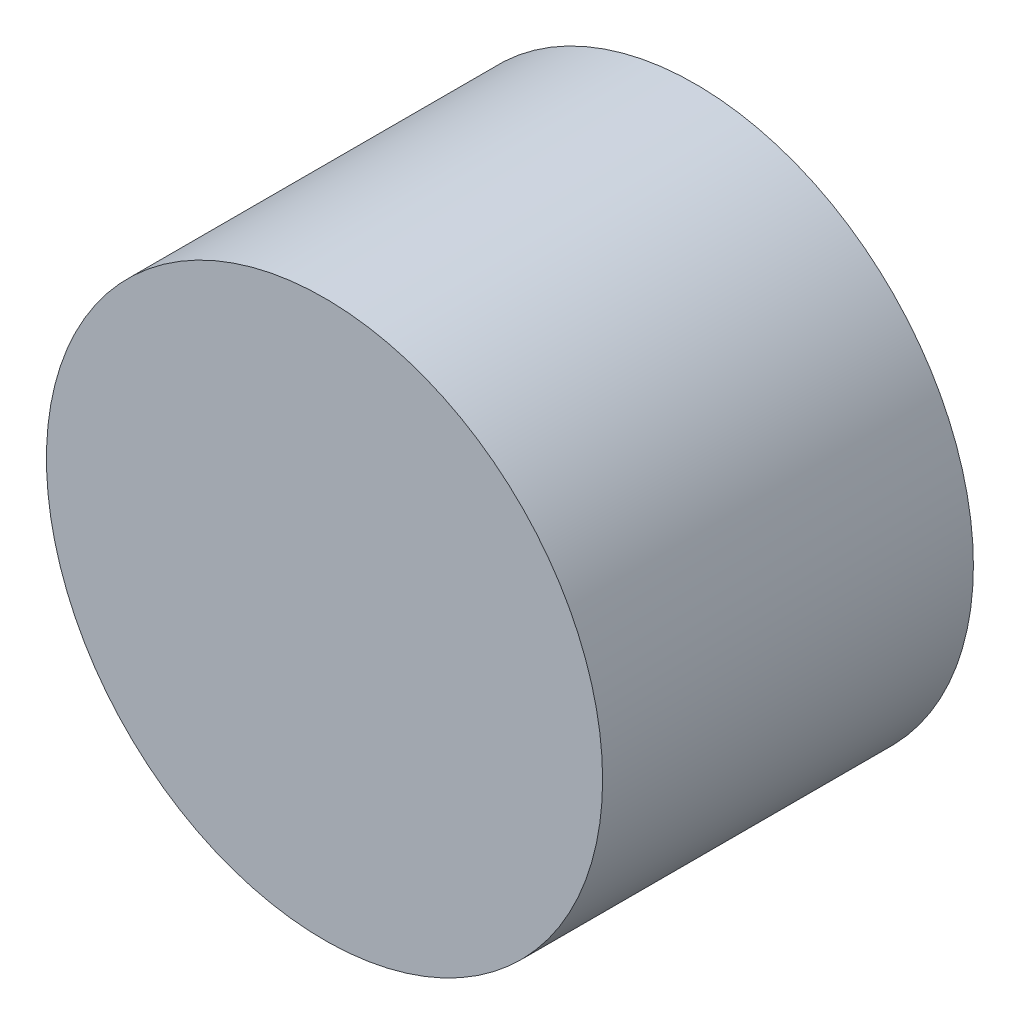
SolidWorks part; units mm, degrees
ref_plane "Alzado" through (0, 0, 0) normal (0, 0, 1) x (1, 0, 0)
ref_plane "Planta" through (0, 0, 0) normal (0, 1, 0) x (1, 0, 0)
ref_plane "Vista lateral" through (0, 0, 0) normal (1, 0, 0) x (0, 0, -1)
sketch "Croquis1" plane through (0, 0, 0) normal (0, 0, 1) x (1, 0, 0)
  circle A0 centre (0, 0) radius 30
  dimension "D1" = 60
extrude "Saliente-Extruir1" add sketch "Croquis1" along normal blind 40
